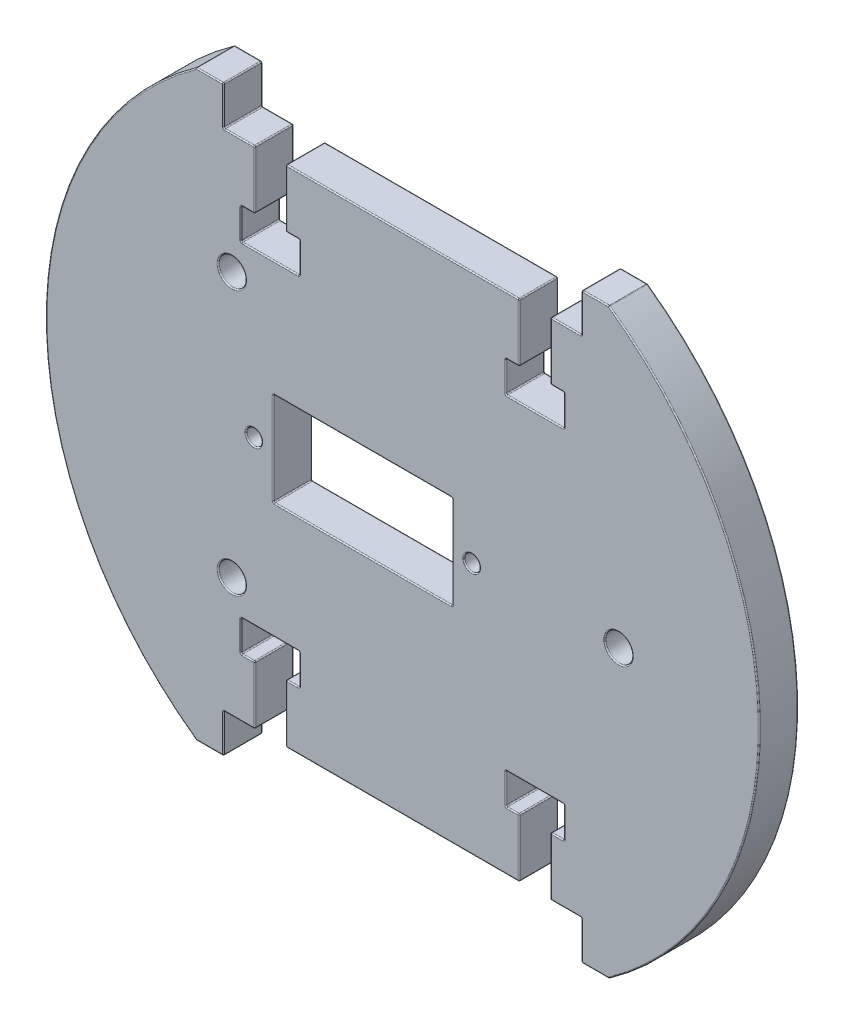
SolidWorks part; units mm, degrees
ref_plane "Front Plane" through (0, 0, 0) normal (0, 0, 1) x (1, 0, 0)
ref_plane "Top Plane" through (0, 0, 0) normal (0, 1, 0) x (1, 0, 0)
ref_plane "Right Plane" through (0, 0, 0) normal (1, 0, 0) x (0, 0, -1)
sketch "Sketch1" plane through (0, 0, 0) normal (0, 0, 1) x (1, 0, 0)
  line L0 (-115.7829, 0) -> (115.7829, 0)
  line L1 (0, 122.9824) -> (0, -122.9824)
  line L2 (-23, 32.4159) -> (23, 32.4159)
  line L3 (26.4981, 37.4159) -> (23, 37.4159)
  line L4 (-23, 32.4159) -> (-23, 37.4159)
  line L5 (23, 32.4159) -> (23, 37.4159)
  line L6 (-23, 37.4159) -> (-26.4981, 37.4159)
  line L8 (6.3913, 6) -> (-16.6087, 6)
  line L9 (6.3913, 6) -> (6.3913, -6)
  line L10 (-23, -37.4159) -> (-26.4981, -37.4159)
  line L11 (23, -32.4159) -> (23, -37.4159)
  line L12 (-23, -32.4159) -> (-23, -37.4159)
  line L13 (26.4981, -37.4159) -> (23, -37.4159)
  line L14 (-23, -32.4159) -> (23, -32.4159)
  line L15 (6.3913, -6) -> (-16.6087, -6)
  line L16 (-16.6087, 6) -> (-16.6087, -6)
  line L17 (6.3913, 6) -> (-16.6087, -6) construction
  line L18 (6.3913, -6) -> (-16.6087, 6) construction
  line L19 (27.75, 0) -> (27.75, 22.4961) construction
  line L20 (27.75, 0) -> (-21.93, 0) construction
  line L21 (-21.93, -17) -> (-21.93, 17)
  arc A0 (-26.4981, 37.4159) -> (-26.4981, -37.4159) centre (0, 0) ccw
  arc A1 (26.4981, -37.4159) -> (26.4981, 37.4159) centre (0, 0) ccw
  circle A2 centre (8.8913, 0) radius 1
  circle A3 centre (-19.1087, 0) radius 1
  circle A4 centre (-21.93, 17) radius 1.75
  circle A5 centre (-21.93, -17) radius 1.75
  circle A6 centre (27.75, 0) radius 1.75
  point P6 (0, 0)
  point P8 (0, 0)
  point P11 (-5.1087, 0)
  point P34 (-21.93, 0)
  dimension "D1" = 23
  dimension "D7" = 2.5
  dimension "D2" = 5
  dimension "D3" = 23
  dimension "D4" = 12
  dimension "D5" = 23
  dimension "D6" = 6.3913
  dimension "D8" = 2.5
  dimension "D9" = 49.68
extrude "Boss-Extrude1" add sketch "Sketch1" along normal blind 5
sketch "Sketch2" plane through (0, 0, 5) normal (0, 0, 1) x (1, 0, 0)
  line L0 (-23, 32.4159) -> (23, 32.4159) construction
  line L1 (-19, 24.9159) -> (-15, 24.9159)
  line L2 (-19, 24.9159) -> (-19, 32.4159)
  line L3 (-19, 32.4159) -> (-15, 32.4159)
  line L4 (-15, 24.9159) -> (-15, 32.4159)
  line L5 (-19, 24.9159) -> (-15, 32.4159) construction
  line L6 (-19, 32.4159) -> (-15, 24.9159) construction
  line L7 (-23, 32.4159) -> (-23, 37.4159) construction
  line L8 (-20.75, 20.9159) -> (-13.25, 20.9159)
  line L9 (-20.75, 20.9159) -> (-20.75, 24.9159)
  line L10 (-20.75, 24.9159) -> (-13.25, 24.9159)
  line L11 (-13.25, 20.9159) -> (-13.25, 24.9159)
  line L12 (-20.75, 20.9159) -> (-13.25, 24.9159) construction
  line L13 (-20.75, 24.9159) -> (-13.25, 20.9159) construction
  line L14 (0, 32.4159) -> (0, 8.7629)
  line L15 (20.75, 24.9159) -> (13.25, 20.9159) construction
  line L16 (20.75, 20.9159) -> (13.25, 24.9159) construction
  line L17 (19, 32.4159) -> (15, 24.9159) construction
  line L18 (19, 24.9159) -> (15, 32.4159) construction
  line L19 (13.25, 20.9159) -> (13.25, 24.9159)
  line L20 (20.75, 24.9159) -> (13.25, 24.9159)
  line L21 (20.75, 20.9159) -> (20.75, 24.9159)
  line L22 (20.75, 20.9159) -> (13.25, 20.9159)
  line L23 (15, 24.9159) -> (15, 32.4159)
  line L24 (19, 32.4159) -> (15, 32.4159)
  line L25 (19, 24.9159) -> (19, 32.4159)
  line L26 (19, 24.9159) -> (15, 24.9159)
  line L27 (-16.6087, 0) -> (6.3913, 0)
  line L28 (-16.6087, 6) -> (-16.6087, -6) construction
  line L29 (6.3913, 6) -> (6.3913, -6) construction
  line L30 (19, -24.9159) -> (15, -32.4159) construction
  line L31 (19, -32.4159) -> (15, -24.9159) construction
  line L32 (20.75, -20.9159) -> (13.25, -24.9159) construction
  line L33 (20.75, -24.9159) -> (13.25, -20.9159) construction
  line L34 (-20.75, -24.9159) -> (-13.25, -20.9159) construction
  line L35 (-20.75, -20.9159) -> (-13.25, -24.9159) construction
  line L36 (-19, -32.4159) -> (-15, -24.9159) construction
  line L37 (-19, -24.9159) -> (-15, -32.4159) construction
  line L38 (19, -24.9159) -> (15, -24.9159)
  line L39 (19, -24.9159) -> (19, -32.4159)
  line L40 (19, -32.4159) -> (15, -32.4159)
  line L41 (15, -24.9159) -> (15, -32.4159)
  line L42 (20.75, -20.9159) -> (13.25, -20.9159)
  line L43 (20.75, -20.9159) -> (20.75, -24.9159)
  line L44 (20.75, -24.9159) -> (13.25, -24.9159)
  line L45 (13.25, -20.9159) -> (13.25, -24.9159)
  line L46 (-13.25, -20.9159) -> (-13.25, -24.9159)
  line L47 (-20.75, -24.9159) -> (-13.25, -24.9159)
  line L48 (-20.75, -20.9159) -> (-20.75, -24.9159)
  line L49 (-20.75, -20.9159) -> (-13.25, -20.9159)
  line L50 (-15, -24.9159) -> (-15, -32.4159)
  line L51 (-19, -32.4159) -> (-15, -32.4159)
  line L52 (-19, -24.9159) -> (-19, -32.4159)
  line L53 (-19, -24.9159) -> (-15, -24.9159)
  point P0 (-17, 28.6659)
  point P7 (-17, 22.9159)
  point P12 (-19, 28.6659)
  point P26 (17, 22.9159)
  point P27 (17, 28.6659)
  point P50 (17, -28.6659)
  point P51 (17, -22.9159)
  point P52 (-17, -22.9159)
  point P53 (-17, -28.6659)
  point P54 (0, 0)
  point P55 (0, 0)
  line M1 (-23, -32.4159) -> (23, -32.4159)
  line M7 (23, 32.4159) -> (-23, 32.4159)
  dimension "D1" = 4
  dimension "D2" = 4
  dimension "D3" = 7.5
  dimension "D4" = 4
  dimension "D5" = 7.5
  dimension "D6" = 0
extrude "Cut-Extrude1" cut sketch "Sketch2" against normal through all contours L1 L4 L2 M7 | L8 L11 L10 L1 L9 | L22 L21 L20 L19 | L20 L25 L23 M7 | L42 L45 L44 L38 L43 | L38 L41 L39 M1 | L49 L48 L47 L46 | L47 L52 L50 M1
fillet "Fillet2" radius 0.15 154 edges at (-17, -20.9159, 5) (-20.75, -22.9159, 5) (-19.875, -24.9159, 5) (-19, -28.6659, 5) (-15, -28.6659, 5) (-14.125, -24.9159, 5) (-13.25, -22.9159, 5) (-17, -20.9159, 0) (-20.75, -22.9159, 0) (-19.875, -24.9159, 0) (-19, -28.6659, 0) (-15, -28.6659, 0) (-14.125, -24.9159, 0) (-13.25, -22.9159, 0) (-20.75, -20.9159, 2.5) (-20.75, -24.9159, 2.5) (-19, -24.9159, 2.5) (-19, -32.4159, 2.5) (-15, -32.4159, 2.5) (-15, -24.9159, 2.5) (-13.25, -24.9159, 2.5) (-13.25, -20.9159, 2.5) (17, -20.9159, 5) (13.25, -22.9159, 5) (14.125, -24.9159, 5) (15, -28.6659, 5) (19, -28.6659, 5) (19.875, -24.9159, 5) (20.75, -22.9159, 5) (17, -20.9159, 0) (13.25, -22.9159, 0) (14.125, -24.9159, 0) (15, -28.6659, 0) (19, -28.6659, 0) (19.875, -24.9159, 0) (20.75, -22.9159, 0) (13.25, -20.9159, 2.5) (13.25, -24.9159, 2.5) (15, -24.9159, 2.5) (19, -32.4159, 2.5) (19, -24.9159, 2.5) (20.75, -24.9159, 2.5) (20.75, -20.9159, 2.5) (17, 20.9159, 5) (20.75, 22.9159, 5) (19.875, 24.9159, 5) (19, 28.6659, 5) (15, 28.6659, 5) (14.125, 24.9159, 5) (13.25, 22.9159, 5) (17, 20.9159, 0) (20.75, 22.9159, 0) (19.875, 24.9159, 0) (19, 28.6659, 0) (15, 28.6659, 0) (14.125, 24.9159, 0) (13.25, 22.9159, 0) (20.75, 20.9159, 2.5) (20.75, 24.9159, 2.5) (19, 24.9159, 2.5) (19, 32.4159, 2.5) (15, 32.4159, 2.5) (15, 24.9159, 2.5) (13.25, 24.9159, 2.5) (13.25, 20.9159, 2.5) (-19, 28.6659, 5) (-19.875, 24.9159, 5) (-20.75, 22.9159, 5) (-17, 20.9159, 5) (-13.25, 22.9159, 5) (-14.125, 24.9159, 5) (-15, 28.6659, 5) (-19, 28.6659, 0) (-19.875, 24.9159, 0) (-20.75, 22.9159, 0) (-17, 20.9159, 0) (-13.25, 22.9159, 0) (-14.125, 24.9159, 0) (-15, 28.6659, 0) (-19, 24.9159, 2.5) (-20.75, 24.9159, 2.5) (-20.75, 20.9159, 2.5) (-13.25, 20.9159, 2.5) (-13.25, 24.9159, 2.5) (-15, 24.9159, 2.5) (-15, 32.4159, 2.5) (-19, 32.4159, 2.5) (21, -32.4159, 0) (21, -32.4159, 5) (0, -32.4159, 0) (0, -32.4159, 5) (-21, -32.4159, 0) (-21, -32.4159, 5) (23, -34.9159, 0) (23, -34.9159, 5) (24.749, -37.4159, 0) (24.749, -37.4159, 5) (45.8486, 0, 0) (45.8486, 0, 5) (24.749, 37.4159, 0) (24.749, 37.4159, 5) (23, 34.9159, 0) (23, 34.9159, 5) (21, 32.4159, 0) (21, 32.4159, 5) (0, 32.4159, 0) (0, 32.4159, 5) (-21, 32.4159, 0) (-21, 32.4159, 5) (-23, 34.9159, 0) (-23, 34.9159, 5) (-24.749, 37.4159, 0) (-24.749, 37.4159, 5) (-45.8486, 0, 0) (-45.8486, 0, 5) (-24.749, -37.4159, 0) (-24.749, -37.4159, 5) (-23, -34.9159, 0) (-23, -34.9159, 5) (6.3913, 0, 0) (6.3913, 0, 5) (-5.1087, -6, 0) (-5.1087, -6, 5) (-16.6087, 0, 0) (-16.6087, 0, 5) (-5.1087, 6, 0) (-5.1087, 6, 5) (9.8913, 0, 5) (9.8913, 0, 0) (-18.1087, 0, 5) (-18.1087, 0, 0) (-20.18, 17, 5) (-20.18, 17, 0) (29.5, 0, 5) (29.5, 0, 0) (-20.18, -17, 5) (-20.18, -17, 0) (-23, -32.4159, 2.5) (-23, -37.4159, 2.5) (-26.4981, -37.4159, 2.5) (-26.4981, 37.4159, 2.5) (-23, 37.4159, 2.5) (-23, 32.4159, 2.5) (23, 32.4159, 2.5) (23, 37.4159, 2.5) (26.4981, 37.4159, 2.5) (26.4981, -37.4159, 2.5) (23, -37.4159, 2.5) (23, -32.4159, 2.5) (6.3913, 6, 2.5) (-16.6087, 6, 2.5) (-16.6087, -6, 2.5) (6.3913, -6, 2.5) (15, -32.4159, 2.5)
